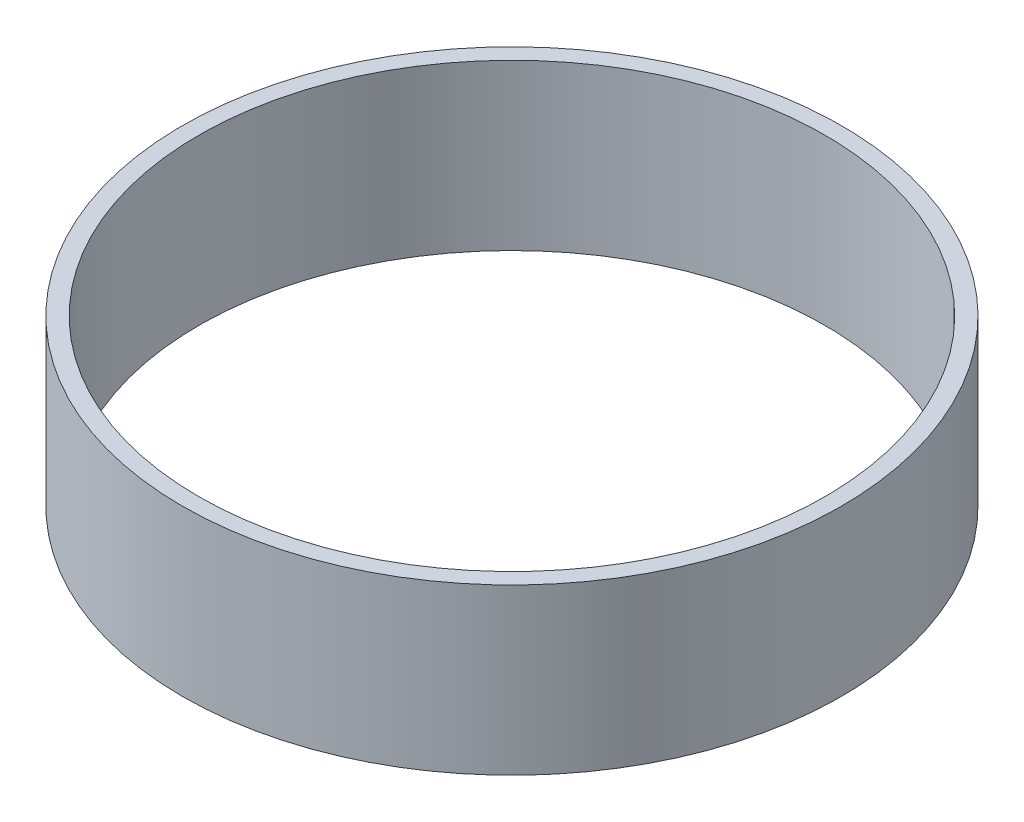
SolidWorks part; units mm, degrees
ref_plane "Front Plane" through (0, 0, 0) normal (0, 0, 1) x (1, 0, 0)
ref_plane "Top Plane" through (0, 0, 0) normal (0, 1, 0) x (1, 0, 0)
ref_plane "Right Plane" through (0, 0, 0) normal (1, 0, 0) x (0, 0, -1)
sketch "Sketch1" plane through (0, 0, 0) normal (0, 1, 0) x (1, 0, 0)
  circle A0 centre (0, 0) radius 50.8
  circle A1 centre (0, 0) radius 48.26
  dimension "D1" = 101.6
  dimension "D2" = 2.54
extrude "Boss-Extrude1" add sketch "Sketch1" along normal blind 25.4
